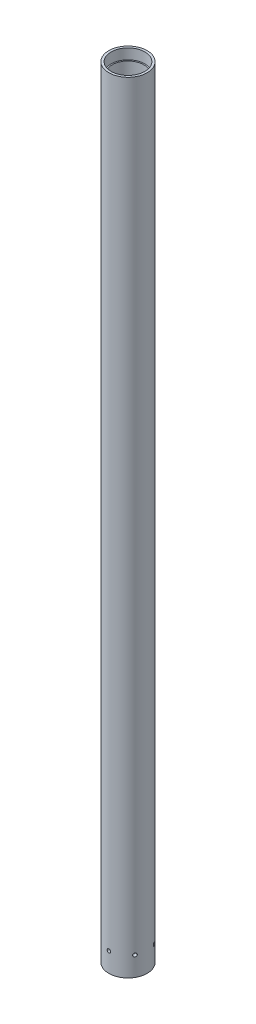
SolidWorks part; units mm, degrees
ref_plane "Front Plane" through (0, 0, 0) normal (0, 0, 1) x (1, 0, 0)
ref_plane "Top Plane" through (0, 0, 0) normal (0, 1, 0) x (1, 0, 0)
ref_plane "Right Plane" through (0, 0, 0) normal (1, 0, 0) x (0, 0, -1)
sketch "Sketch1" plane through (0, 0, 0) normal (0, 1, 0) x (1, 0, 0)
  circle A0 centre (0, 0) radius 14.75
  circle A1 centre (0, 0) radius 12
  dimension "D1" = 29.5
  dimension "D2" = 24
extrude "Boss-Extrude1" add sketch "Sketch1" along normal blind 600
sketch "Sketch2" plane through (0, 600, 0) normal (0, 1, 0) x (1, 0, 0)
  line L0 (0, 0) -> (0, 14.75) construction
  line L1 (0, 0) -> (0, -14.75) construction
  circle A0 centre (0, 0) radius 14.75 construction
ref_plane "Plane1" through (0, 0, 14.75) normal (0, 0, 1) x (1, 0, 0)
sketch "Sketch4" plane through (0, 0, 14.75) normal (0, 0, 1) x (1, 0, 0)
  line L0 (-14.75, 0) -> (14.75, 0) construction
  circle A0 centre (0, 15) radius 1.325
  point P5 (0, 0)
  dimension "D1" = 2.65
  dimension "D2" = 15
extrude "Cut-Extrude2" cut sketch "Sketch4" against normal blind 10
pattern_circular "CirPattern2" count 4 every 60 about axis through (0, 600, 0) along (0, -1, 0) of "Cut-Extrude2"
sketch "Sketch5" plane through (0, 0, 0) normal (0, -1, 0) x (1, 0, 0)
  circle A0 centre (0, 0) radius 12
  circle A1 centre (0, 0) radius 13
  dimension "D1" = 24
  dimension "D2" = 26
extrude "Cut-Extrude3" cut sketch "Sketch5" against normal blind 8
pattern_linear "LPattern1" count 2 spacing 592 along (0, 1, 0) of "Cut-Extrude3"
